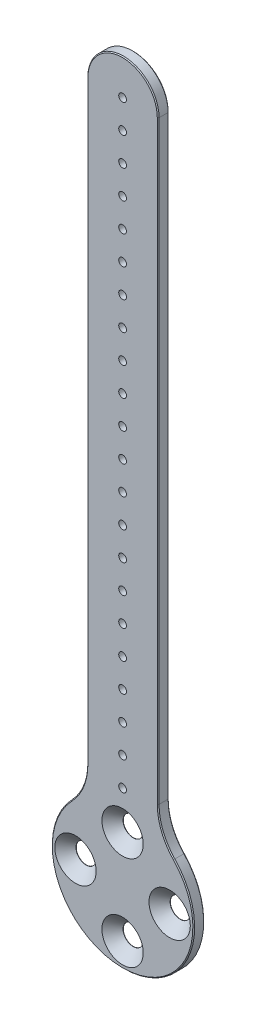
SolidWorks part; units mm, degrees
material "Plain Carbon Steel"
ref_plane "Front Plane" through (0, 0, 0) normal (0, 0, 1) x (1, 0, 0)
ref_plane "Top Plane" through (0, 0, 0) normal (0, 1, 0) x (1, 0, 0)
ref_plane "Right Plane" through (0, 0, 0) normal (1, 0, 0) x (0, 0, -1)
sketch "Sketch1" plane through (0, 0, 0) normal (0, 0, 1) x (1, 0, 0)
  line L0 (0, 0) -> (0, 304.8) construction
  line L2 (15.875, 27.4963) -> (15.875, 304.8)
  line L5 (-15.875, 27.4963) -> (-15.875, 304.8)
  arc A0 (-15.875, 27.4963) -> (15.875, 27.4963) centre (0, 0) ccw
  arc A1 (-15.875, 304.8) -> (15.875, 304.8) centre (0, 304.8) cw
  point P1 (0, -31.75)
  dimension "D1" = 63.5
  dimension "D2" = 15.875
  dimension "D3" = 336.55
extrude "Boss-Extrude1" add sketch "Sketch1" along normal blind 4.826
fillet "Fillet1" radius 25.4 2 edges at (-15.875, 27.4963, 2.413) (15.875, 27.4963, 2.413)
hole_wizard "#8-32 Tapped Hole1" positions "Sketch2" profile "Sketch3" tap size "#8-32" standard "ANSI Inch"
sketch "Sketch2" plane through (0, 0, 4.826) normal (0, 0, 1) x (1, 0, 0)
  point P0 (0, 304.8)
sketch "Sketch3" plane through (0, 304.8, 4.826) normal (1, 0, 0) x (0, -1, 0)
  line L0 (0, 0) -> (0, 11.7058)
  line L1 (0, 11.7058) -> (1.7272, 10.668)
  line L2 (1.7272, 10.668) -> (1.7272, 0)
  line L5 (1.7272, 0) -> (0, 0)
  line L10 (0, 11.7058) -> (-1.7272, 10.668) construction
  line L11 (0, -6.35) -> (0, 107.95) construction
  dimension "Tap Drill Dia." = 3.4544
  dimension "Tap Drill Depth" = 10.668
  dimension "Drill Angle" = 118
cosmetic thread "Hole Thread1" parameters "D1"=4.826, "D2"=4.1656
pattern_linear "LPattern1" count 22 spacing 12.7 along (0, -1, 0) of "#8-32 Tapped Hole1"
sketch "Sketch4" plane through (0, 0, 4.826) normal (0, 0, 1) x (1, 0, 0)
  circle A0 centre (0, 0) radius 21
sketch "Sketch5" plane through (0, 0, 4.826) normal (0, 0, 1) x (1, 0, 0)
  line L0 (0, 0) -> (0, -14.986) construction
  line L1 (0, 0) -> (-12.9783, 7.493) construction
  line L2 (0, 0) -> (12.9783, 7.493) construction
  circle A0 centre (0, 0) radius 14.986
  circle A1 centre (0, -14.986) radius 2.75
  circle A2 centre (-12.9783, 7.493) radius 2.75
  circle A3 centre (12.9783, 7.493) radius 2.75
  point P11 (0, 0)
  dimension "D1" = 29.972
  dimension "D2" = 5.5
  dimension "D3" = 3
  dimension "D4" = 120
  dimension "D5" = 120
hole_wizard "CSK for M8 SFHCS1" positions "Sketch6" profile "Sketch7" countersink size "M8" standard "ANSI Metric"
sketch "Sketch6" plane through (0, 0, 4.826) normal (0, 0, 1) x (1, 0, 0)
  circle A0 centre (0, 0) radius 21 construction
  point P0 (0, -21)
sketch "Sketch7" plane through (0, -21, 4.826) normal (1, 0, 0) x (0, -1, 0)
  line L0 (0, 0) -> (0, 28.1039)
  line L1 (0, 28.1039) -> (4.5, 25.4)
  line L2 (4.5, 25.4) -> (4.5, 4.714)
  line L3 (4.5, 4.714) -> (9.214, 0)
  line L5 (9.214, 0) -> (0, 0)
  line L6 (-4.5, 4.714) -> (-9.214, 0) construction
  line L10 (0, 28.1039) -> (-4.5, 25.4) construction
  line L11 (0, -6.35) -> (0, 107.95) construction
  dimension "Hole Dia." = 9
  dimension "Hole Depth" = 25.4
  dimension "Near C'Sink Dia." = 18.428
  dimension "Near C'Sink Angle" = 90
  dimension "Drill Angle" = 118
pattern_circular "CirPattern1" count 4 over 360 about axis through (0, 0, 0) along (0, 0, 1) of "CSK for M8 SFHCS1"
chamfer "Chamfer1" distance 0.3969 angle 45 12 edges at (-15.875, 172.1642, 0) (0, 320.675, 0) (-17.7048, 30.0624, 0) (15.875, 172.1642, 0) (0, -31.75, 0) (17.7048, 30.0624, 0) (-15.875, 172.1642, 4.826) (-17.7048, 30.0624, 4.826) (0, 320.675, 4.826) (0, -31.75, 4.826) (15.875, 172.1642, 4.826) (17.7048, 30.0624, 4.826)
sketch "Sketch8" plane through (0, 0, 4.826) normal (0, 0, 1) x (1, 0, 0)
  line L0 (0, 304.8) -> (0, 0) construction
